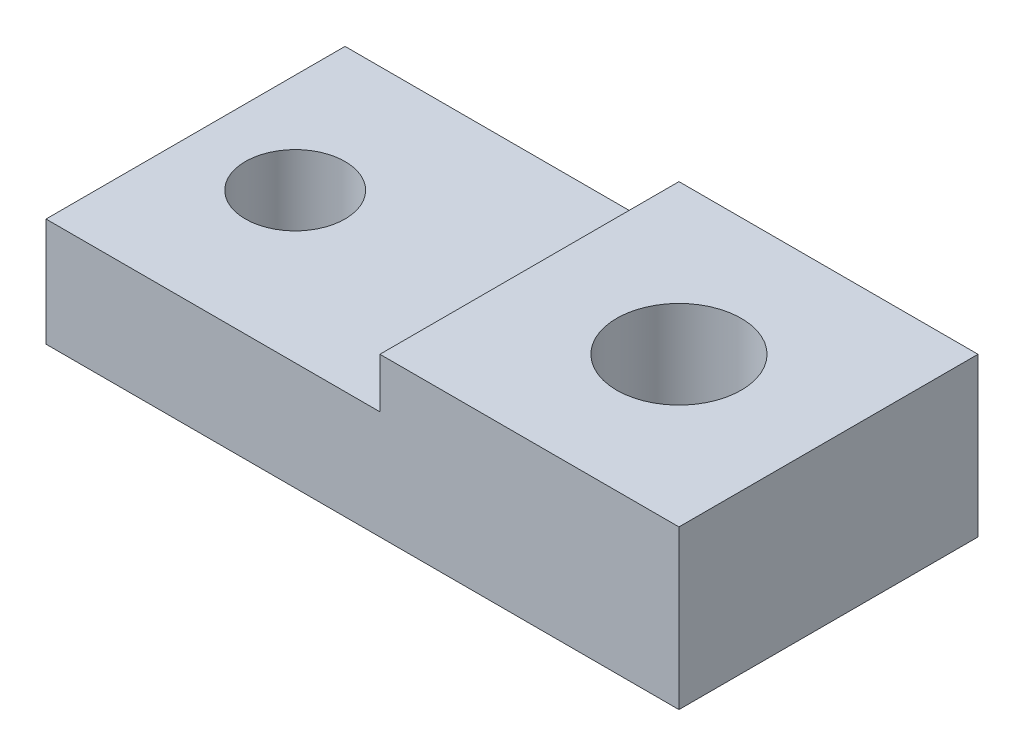
SolidWorks part; units mm, degrees
material "Copper"
ref_plane "Front Plane" through (0, 0, 0) normal (0, 0, 1) x (1, 0, 0)
ref_plane "Top Plane" through (0, 0, 0) normal (0, 1, 0) x (1, 0, 0)
ref_plane "Right Plane" through (0, 0, 0) normal (1, 0, 0) x (0, 0, -1)
sketch "Sketch1" plane through (0, 0, 0) normal (0, 1, 0) x (1, 0, 0)
  line L1 (-6.35, -3) -> (6.35, -3)
  line L2 (-6.35, -3) -> (-6.35, 3)
  line L3 (-6.35, 3) -> (6.35, 3)
  line L4 (6.35, -3) -> (6.35, 3)
  line L5 (-6.35, -3) -> (6.35, 3) construction
  line L6 (-6.35, 3) -> (6.35, -3) construction
  point P0 (0, 0)
  point P6 (3.35, 0)
  dimension "D1" = 12.7
  dimension "D2" = 6
  dimension "D3" = 3
extrude "Boss-Extrude1" add sketch "Sketch1" along normal mid plane 3.175
hole_wizard "M3x0.5 Tapped Hole1" positions "Sketch2" profile "Sketch3" tap size "M3x0.5" standard "ANSI Metric" end condition through all
sketch "Sketch2" plane through (0, 1.5875, 0) normal (0, 1, 0) x (1, 0, 0)
  point P0 (3.35, 0)
sketch "Sketch3" plane through (3.35, 1.5875, 0) normal (1, 0, 0) x (0, 0, 1)
  line L0 (0, 0) -> (0, 3.175)
  line L1 (0, 3.175) -> (1.25, 3.175)
  line L2 (1.25, 3.175) -> (1.25, 0)
  line L5 (1.25, 0) -> (0, 0)
  line L11 (0, -6.35) -> (0, 107.95) construction
  dimension "Thru Tap Drill Dia." = 2.5
  dimension "Thru Tap Drill Depth" = 3.175
cosmetic thread "Hole Thread1" parameters "D2"=3
sketch "Sketch4" plane through (0, 0, 3) normal (0, 0, 1) x (1, 0, 0)
  line L0 (-6.35, 1.5875) -> (6.35, 1.5875) construction
  line L1 (-6.35, 1.5875) -> (0.35, 1.5875)
  line L2 (-6.35, 1.5875) -> (-6.35, 0.5875)
  line L3 (-6.35, 0.5875) -> (0.35, 0.5875)
  line L4 (0.35, 1.5875) -> (0.35, 0.5875)
  line L6 (-6.35, 1.5875) -> (-6.35, -1.5875) construction
  line L7 (6.35, 1.5875) -> (6.35, -1.5875) construction
  dimension "D1" = 1
  dimension "D2" = 6
extrude "Cut-Extrude1" cut sketch "Sketch4" against normal through all
sketch "Sketch5" plane through (0, 0.5875, 0) normal (0, 1, 0) x (1, 0, 0)
  line L0 (-6.35, 3) -> (-6.35, -3) construction
  circle A0 centre (-4.35, 0) radius 1
  dimension "D1" = 2
  dimension "D2" = 2
extrude "Cut-Extrude2" cut sketch "Sketch5" against normal through all
equation "\"D1@Sketch1\"=0.5in"
